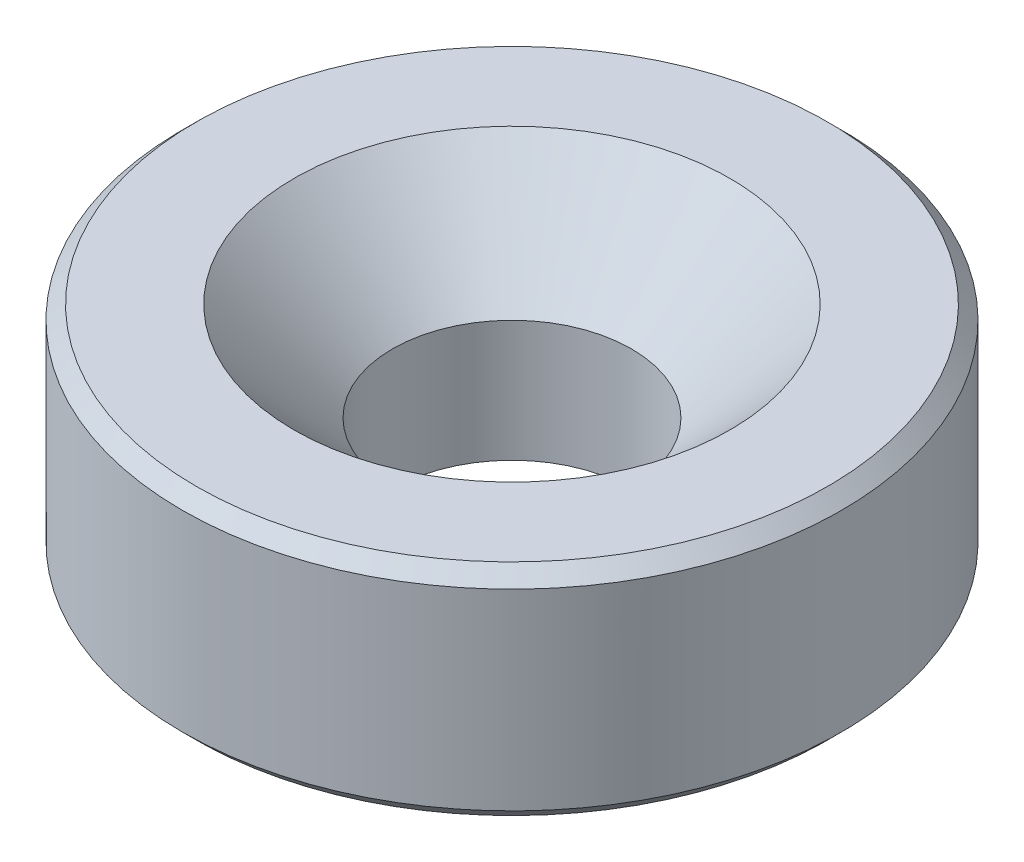
SolidWorks part; units mm, degrees
ref_plane "Front Plane" through (0, 0, 0) normal (0, 0, 1) x (1, 0, 0)
ref_plane "Top Plane" through (0, 0, 0) normal (0, 1, 0) x (1, 0, 0)
ref_plane "Right Plane" through (0, 0, 0) normal (1, 0, 0) x (0, 0, -1)
sketch "Sketch1" plane through (0, 0, 0) normal (0, 0, 1) x (1, 0, 0)
  line L0 (-1.7272, 0) -> (-1.7272, 1.7522)
  line L1 (-1.7272, 1.7522) -> (-3.15, 3.175)
  line L2 (-3.15, 3.175) -> (-4.7625, 3.175)
  line L3 (-4.7625, 3.175) -> (-4.7625, 0)
  line L4 (-4.7625, 0) -> (-1.7272, 0)
  line L5 (0, 0) -> (0, -11354.7903) construction
  dimension "D1" = 9.525
  dimension "D2" = 3.4544
  dimension "D3" = 3.175
  dimension "D4" = 45
  dimension "D5" = 6.3
revolve "Revolve1" add sketch "Sketch1" angle 360 about L5
chamfer "Chamfer1" distance 0.2 angle 45 2 edges at (0, 0, 4.7625) (0, 3.175, 4.7625)
